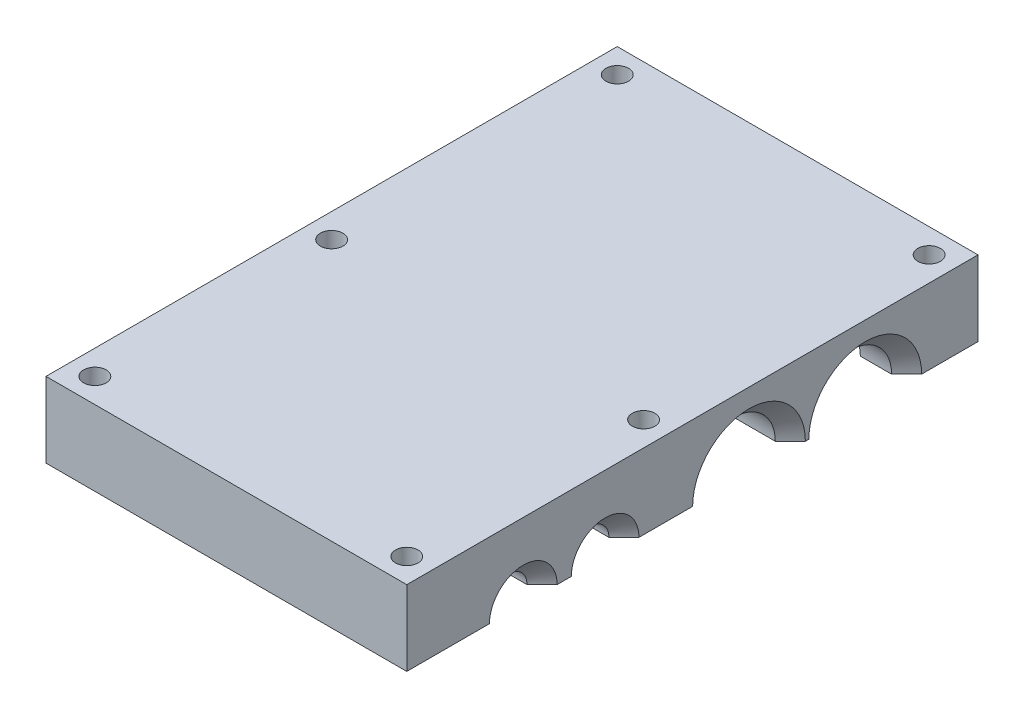
SolidWorks part; units mm, degrees
material "POM Acetal Copolymer"
ref_plane "Front Plane" through (0, 0, 0) normal (0, 0, 1) x (1, 0, 0)
ref_plane "Top Plane" through (0, 0, 0) normal (0, 1, 0) x (1, 0, 0)
ref_plane "Right Plane" through (0, 0, 0) normal (1, 0, 0) x (0, 0, -1)
sketch "Sketch1" plane through (0, 0, 0) normal (0, 1, 0) x (1, 0, 0)
  line L0 (-24, 38) -> (-24, -38)
  line L1 (-24, 38) -> (24, 38)
  line L2 (-24, -38) -> (24, -38)
  line L3 (24, 38) -> (24, -38)
  line L4 (-24, 38) -> (24, -38) construction
  line L5 (-24, -38) -> (24, 38) construction
  point P1 (0, 0)
  dimension "D1" = 48
  dimension "D2" = 76
extrude "Boss-Extrude1" add sketch "Sketch1" along normal blind 10
sketch "Sketch2" plane through (-24, 0, 0) normal (-1, 0, 0) x (0, 0, 1)
  line L1 (-38, 10) -> (38, 10) construction
  circle A0 centre (-23, 10) radius 5.5
  circle A1 centre (-7.5312, 10) radius 5.5
  circle A2 centre (11.6088, 10) radius 2.5
  circle A3 centre (22.5, 10) radius 2.5
  dimension "D1" = 5
  dimension "D2" = 11
  dimension "D3" = 10.8912
  dimension "D4" = 15.4688
  dimension "D5" = 15
  dimension "D6" = 15.5
extrude "Cut-Extrude1" cut sketch "Sketch2" against normal through all
sketch "Sketch3" plane through (-24, 0, 0) normal (-1, 0, 0) x (0, 0, 1)
  line L0 (-30.5756, 16.8073) -> (-30.5756, 2.2109)
  line L1 (-30.5756, 2.2109) -> (-22.8406, 2.2109)
  line L2 (6.1247, 18.1956) -> (6.1247, 4.5924)
  line L3 (6.1247, 4.5924) -> (11.6088, 4.5924)
  line L4 (-30.5756, 16.8073) -> (-10.9415, 16.8073)
  line L5 (6.1247, 18.1956) -> (26.069, 13.9761)
  line L6 (-5.0505, 16.8073) -> (-26.9356, 16.8073) construction
  line L7 (-30.5756, 5.8509) -> (-30.5756, 13.1673) construction
  line L8 (6.1247, 12.921) -> (6.1247, 7.7701) construction
  arc A0 (18.5907, 6.0584) -> (26.069, 13.9761) centre (22.3078, 10.0381) ccw
  arc A1 (-12.7389, 4.3772) -> (-10.9415, 16.8073) centre (-7.3706, 9.9459) ccw
  arc A2 (-22.8406, 2.2109) -> (-17.4723, 4.3772) centre (-22.8406, 9.9459) ccw
  arc A3 (-17.4723, 4.3772) -> (-12.7389, 4.3772) centre (-15.1056, 1.9222) cw
  arc A4 (-16.1312, 8.6953) -> (-17.5589, 14.2684) centre (-22.8406, 9.9459) ccw construction
  arc A7 (-12.7377, 4.376) -> (-2.7067, 16.1167) centre (-7.3706, 9.9459) ccw construction
  arc A9 (11.6088, 4.5924) -> (15.3075, 6.0553) centre (11.6088, 10) ccw
  arc A10 (15.3075, 6.0553) -> (18.5907, 6.0584) centre (16.9508, 4.3027) cw
  arc A12 (25.5913, 5.6937) -> (18.5292, 13.9594) centre (22.3078, 10.0381) ccw construction
  arc A13 (15.1952, 13.9594) -> (18.5292, 13.9594) centre (16.8622, 15.6894) ccw construction
  arc A14 (9.1088, 10) -> (14.1088, 10) centre (11.6088, 10) ccw construction
  dimension "D1" = 3.41
extrude "Cut-Extrude2" cut sketch "Sketch3" against normal blind 40
fillet "Fillet1" radius 3.6 1 edges at (-4, 2.2109, -30.5756)
fillet "Fillet2" radius 2.5 1 edges at (-4, 4.5924, 6.1247)
hole_wizard "M3 Tapped Hole1" positions "Sketch5" profile "Sketch4" tap size "M3" standard "ISO" end condition through all
sketch "Sketch5" plane through (0, 10, 0) normal (0, 1, 0) x (1, 0, 0)
  line L0 (20.75, -3.2445) -> (-20.75, -3.2445) construction
  line L1 (24, -38) -> (24, -25) construction
  line L2 (-24, -38) -> (24, -38) construction
  line L3 (24, 38) -> (-24, 38) construction
  line L4 (-24, 38) -> (-24, 30.5756) construction
  line L5 (-24, -3.2445) -> (-20.75, -3.2445) construction
  line L6 (-24, -0.3642) -> (-24, -6.1247) construction
  circle A0 centre (20.75, -34.75) radius 3.25 construction
  circle A1 centre (-20.75, 34.75) radius 3.25 construction
  point P0 (-20.75, 34.75)
  point P2 (20.75, 34.75)
  point P4 (20.75, -3.2445)
  point P6 (-20.75, -3.2445)
  point P8 (-20.75, -34.75)
  point P10 (20.75, -34.75)
  dimension "D1" = 6.5
sketch "Sketch4" plane through (-20.75, 10, -34.75) normal (1, 0, 0) x (0, 0, 1)
  line L0 (0, 0) -> (0, 10)
  line L1 (0, 10) -> (1.25, 10)
  line L2 (1.25, 10) -> (1.25, 0.275)
  line L3 (1.25, 0.275) -> (1.525, 0)
  line L5 (1.525, 0) -> (0, 0)
  line L6 (-1.25, 0.275) -> (-1.525, 0) construction
  line L11 (0, -6.35) -> (0, 107.95) construction
  dimension "Thread Major Dia." = 2.5
  dimension "Thru Tap Drill Depth" = 10
  dimension "Near C'Sink Dia." = 3.05
  dimension "Near C'Sink Angle" = 90
chamfer "Chamfer1" distance 2 angle 45 12 edges at (-24, 8.5462, 6.1247) (-24, 5.3247, 6.857) (-24, 5.0357, 24.4598) (-24, 4.5924, 10.1168) (-24, 6.7052, 16.9485) (-24, 4.9714, 13.5975) (-24, 7.9055, -30.5756) (-24, 3.2653, -29.5212) (-24, 2.8378, -4.3203) (-24, 2.2109, -24.9081) (-24, 5.3322, -15.1056) (-24, 2.7729, -19.9461)
mirror "Mirror1" about plane through (0, 10, 0) normal (0, -1, 0) of bodies 104
delete or keep bodies "Body-Delete/Keep 1" type delete bodies bodies 104
sketch "Sketch6" plane through (0, 20, 0) normal (0, 1, 0) x (1, 0, 0)
  circle A0 centre (20.75, 34.75) radius 1.5
  circle A1 centre (-20.75, 34.75) radius 1.5
  circle A2 centre (-20.75, -3.2445) radius 1.5
  circle A3 centre (20.75, -3.2445) radius 1.5
  circle A4 centre (20.75, -34.75) radius 1.5
  circle A6 centre (-20.75, -34.75) radius 1.5
  dimension "D1" = 3
extrude "Cut-Extrude3" cut sketch "Sketch6" against normal blind 10
sketch "Sketch7" plane through (16, 0, 0) normal (-1, 0, 0) x (0, 0, 1)
  line L5 (6.1247, 12.9076) -> (6.1247, 10)
  line L6 (6.1247, 10) -> (9.1088, 10)
  line L7 (14.1088, 10) -> (20, 10)
  line L8 (25, 10) -> (27.7533, 10)
  line L9 (11.6088, 15.4076) -> (8.6247, 15.4076)
  line L10 (6.1247, 12.9076) -> (6.1247, 10)
  line L11 (6.1247, 10) -> (9.1088, 10)
  line L12 (14.1088, 10) -> (20, 10)
  line L13 (25, 10) -> (27.7533, 10)
  line L14 (11.6088, 15.4076) -> (8.6247, 15.4076)
  arc A6 (14.1088, 10) -> (9.1088, 10) centre (11.6088, 10) ccw
  arc A7 (25, 10) -> (20, 10) centre (22.5, 10) ccw
  arc A8 (27.7533, 10) -> (18.5907, 13.9416) centre (22.3078, 9.9619) ccw
  arc A9 (15.3075, 13.9447) -> (18.5907, 13.9416) centre (16.9508, 15.6973) ccw
  arc A10 (15.3075, 13.9447) -> (11.6088, 15.4076) centre (11.6088, 10) ccw
  arc A11 (8.6247, 15.4076) -> (6.1247, 12.9076) centre (8.6247, 12.9076) ccw
  arc A12 (14.1088, 10) -> (9.1088, 10) centre (11.6088, 10) ccw
  arc A13 (25, 10) -> (20, 10) centre (22.5, 10) ccw
  arc A14 (27.7533, 10) -> (18.5907, 13.9416) centre (22.3078, 9.9619) ccw
  arc A15 (15.3075, 13.9447) -> (18.5907, 13.9416) centre (16.9508, 15.6973) ccw
  arc A16 (15.3075, 13.9447) -> (11.6088, 15.4076) centre (11.6088, 10) ccw
  arc A17 (8.6247, 15.4076) -> (6.1247, 12.9076) centre (8.6247, 12.9076) ccw
  dimension "D1" = 0
extrude "Boss-Extrude2" add sketch "Sketch7" along normal blind 6.8
chamfer "Chamfer2" distance 2 angle 45 4 edges at (24, 12.5, 22.5) (24, 12.5, 11.6088) (24, 15.5, -7.5312) (24, 15.5, -23)
sketch "Sketch8" plane through (0, 10, 0) normal (0, -1, 0) x (1, 0, 0)
  line L0 (24, -30.5) -> (24, -38) construction
  line L1 (17.8437, -56.1478) -> (14.8437, -56.1478)
  line L2 (17.8437, -56.1478) -> (17.8437, -22.5535)
  line L3 (17.8437, -22.5535) -> (14.8437, -22.5535)
  line L4 (14.8437, -56.1478) -> (14.8437, -22.5535)
  dimension "D1" = 3
  dimension "D2" = 6.1563
extrude "Cut-Extrude4" cut sketch "Sketch8" against normal blind 5
